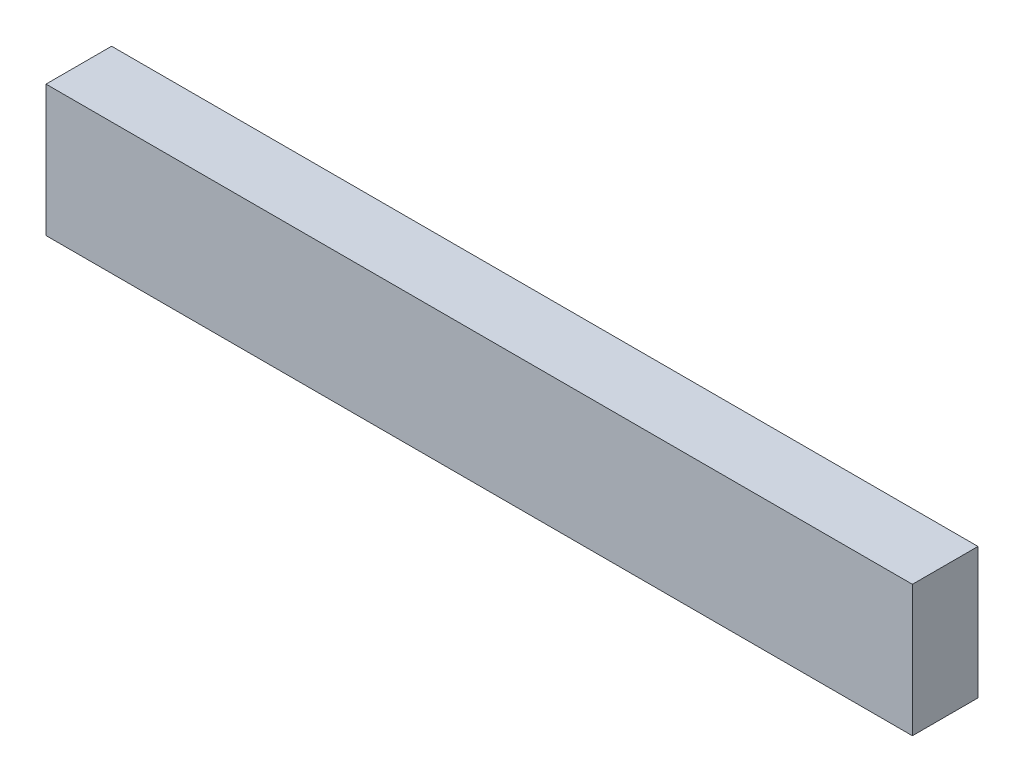
SolidWorks part; units mm, degrees
ref_plane "Front Plane" through (0, 0, 0) normal (0, 0, 1) x (1, 0, 0)
ref_plane "Top Plane" through (0, 0, 0) normal (0, 1, 0) x (1, 0, 0)
ref_plane "Right Plane" through (0, 0, 0) normal (1, 0, 0) x (0, 0, -1)
sketch "Sketch1" plane through (0, 0, 0) normal (0, 1, 0) x (1, 0, 0)
  line L1 (0, 0) -> (1320.8, 0)
  line L2 (0, 0) -> (0, 100)
  line L3 (0, 100) -> (1320.8, 100)
  line L4 (1320.8, 0) -> (1320.8, 100)
  dimension "D1" = 1320.8
  dimension "D2" = 100
extrude "Boss-Extrude1" add sketch "Sketch1" along normal blind 200
